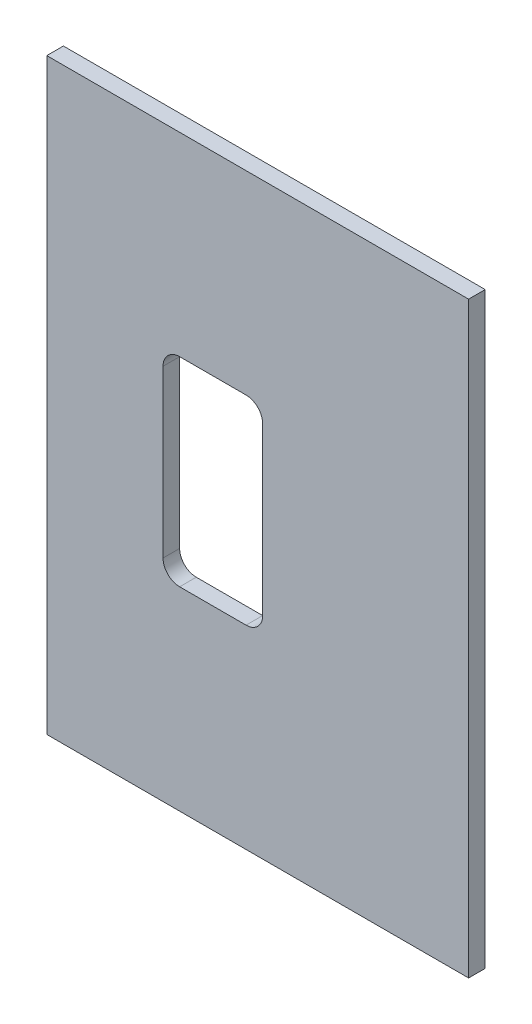
SolidWorks part; units mm, degrees
ref_plane "Front Plane" through (0, 0, 0) normal (0, 0, 1) x (1, 0, 0)
ref_plane "Top Plane" through (0, 0, 0) normal (0, 1, 0) x (1, 0, 0)
ref_plane "Right Plane" through (0, 0, 0) normal (1, 0, 0) x (0, 0, -1)
sketch "Sketch1" plane through (0, 0, 0) normal (0, 0, 1) x (1, 0, 0)
  line L1 (-40.3225, -56.1975) -> (40.3225, -56.1975)
  line L2 (-40.3225, -56.1975) -> (-40.3225, 56.1975)
  line L3 (-40.3225, 56.1975) -> (40.3225, 56.1975)
  line L4 (40.3225, -56.1975) -> (40.3225, 56.1975)
  line L5 (-40.3225, -56.1975) -> (40.3225, 56.1975) construction
  line L6 (-40.3225, 56.1975) -> (40.3225, -56.1975) construction
  line L7 (-18.0975, -19.05) -> (-18.0975, 19.05)
  line L8 (-18.0975, 19.05) -> (0.9525, 19.05)
  line L9 (-18.0975, -19.05) -> (0.9525, -19.05)
  line L10 (0.9525, 19.05) -> (0.9525, -19.05)
  point P0 (0, 0)
extrude "Boss-Extrude1" add sketch "Sketch1" along normal blind 3.175
fillet "Fillet1" radius 3.175 4 edges at (-18.0975, -19.05, 1.5875) (0.9525, -19.05, 1.5875) (0.9525, 19.05, 1.5875) (-18.0975, 19.05, 1.5875)
